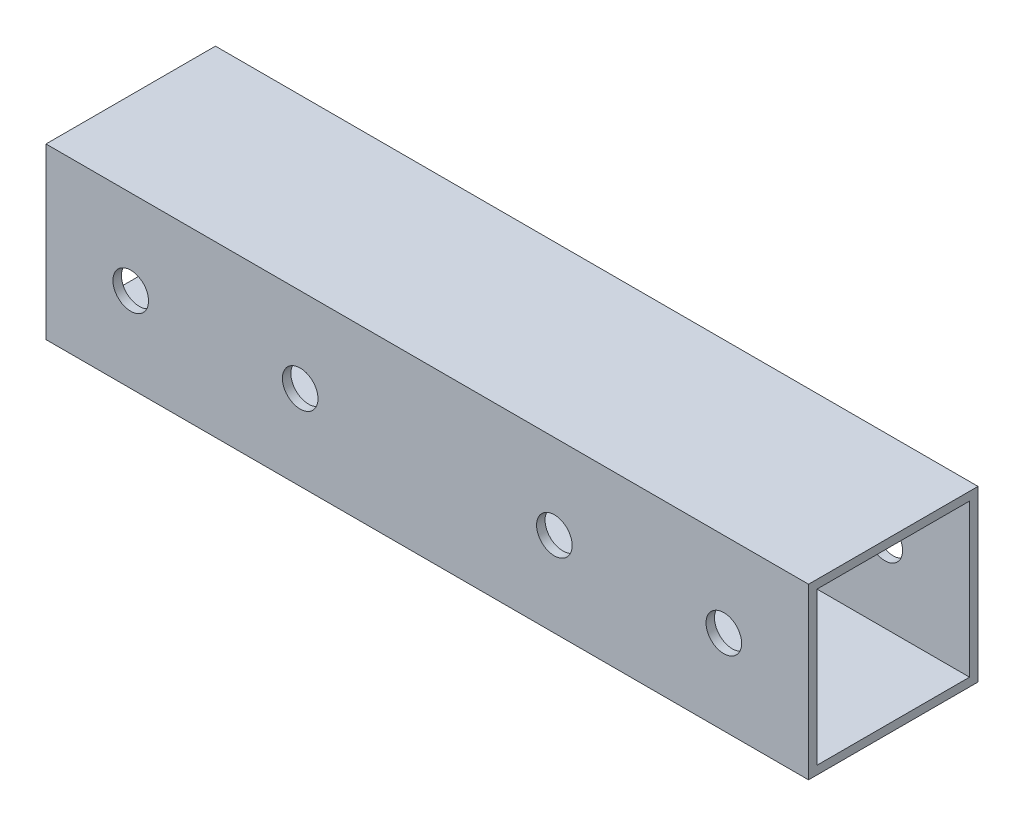
SolidWorks part; units mm, degrees
ref_plane "前视基准面" through (0, 0, 0) normal (0, 0, 1) x (1, 0, 0)
ref_plane "上视基准面" through (0, 0, 0) normal (0, 1, 0) x (1, 0, 0)
ref_plane "右视基准面" through (0, 0, 0) normal (1, 0, 0) x (0, 0, -1)
sketch "草图1" plane through (0, 0, 0) normal (1, 0, 0) x (0, 0, -1)
  line L1 (-10, 10) -> (10, 10)
  line L2 (-10, 10) -> (-10, -10)
  line L3 (-10, -10) -> (10, -10)
  line L4 (10, 10) -> (10, -10)
  line L5 (-10, 10) -> (10, -10) construction
  line L6 (-10, -10) -> (10, 10) construction
  point P0 (0, 0)
  dimension "D1" = 20
  dimension "D2" = 20
extrude "凸台-拉伸1" add sketch "草图1" along normal blind 90
sketch "草图2" plane through (0, 0, 10) normal (0, 0, 1) x (1, 0, 0)
  line L0 (90, 10) -> (0, 10) construction
  line L1 (0, 10) -> (0, -10) construction
  line L2 (45, 10) -> (45, -10) construction
  line L3 (90, -10) -> (0, -10) construction
  circle A0 centre (10, 0) radius 2.1
  circle A2 centre (30, 0) radius 2.1
  circle A3 centre (60, 0) radius 2.1
  circle A4 centre (80, 0) radius 2.1
  dimension "D1" = 4.2
  dimension "D2" = 10
  dimension "D3" = 10
  dimension "D5" = 20
  dimension "D4" = 2
extrude "切除-拉伸1" cut sketch "草图2" against normal through all
sketch "草图3" plane through (0, 0, 0) normal (-1, 0, 0) x (0, 0, 1)
  line L1 (-9, 9) -> (9, 9)
  line L2 (-9, 9) -> (-9, -9)
  line L3 (-9, -9) -> (9, -9)
  line L4 (9, 9) -> (9, -9)
  line L5 (-9, 9) -> (9, -9) construction
  line L6 (-9, -9) -> (9, 9) construction
  point P0 (0, 0)
  dimension "D1" = 18
  dimension "D2" = 18
extrude "切除-拉伸2" cut sketch "草图3" against normal through all
